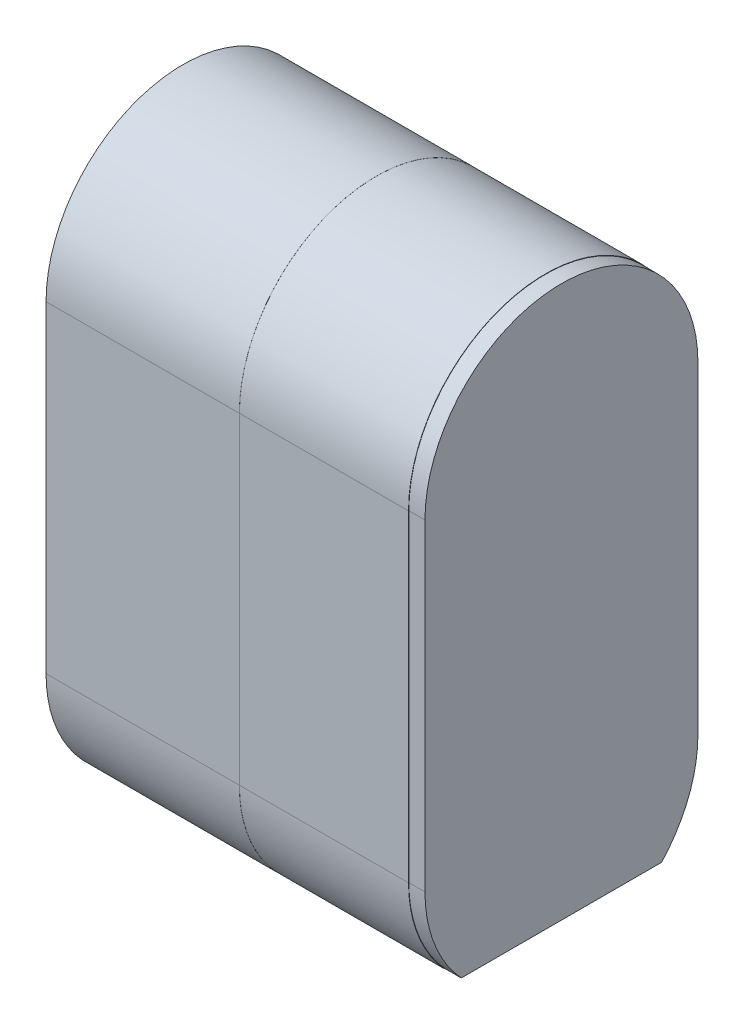
SolidWorks part; units mm, degrees
ref_plane "Front Plane" through (0, 0, 0) normal (0, 0, 1) x (1, 0, 0)
ref_plane "Top Plane" through (0, 0, 0) normal (0, 1, 0) x (1, 0, 0)
ref_plane "Right Plane" through (0, 0, 0) normal (1, 0, 0) x (0, 0, -1)
sketch "Sketch1" plane through (0, 0, 0) normal (1, 0, 0) x (0, 0, -1)
  line L0 (0, 0) -> (0, -40) construction
  line L1 (17, 0) -> (17, -40)
  line L2 (-17, 0) -> (-17, -40)
  line L3 (0, 0) -> (0, -40) construction
  line L4 (15, 0) -> (15, -40)
  line L5 (-15, 0) -> (-15, -40)
  arc A0 (17, 0) -> (-17, 0) centre (0, 0) ccw
  arc A1 (-17, -40) -> (17, -40) centre (0, -40) ccw
  arc A2 (15, 0) -> (-15, 0) centre (0, 0) ccw
  arc A3 (-15, -40) -> (15, -40) centre (0, -40) ccw
  point P3 (0, -20)
  point P8 (0, -20)
  dimension "D1" = 2
  dimension "D2" = 40
  dimension "D3" = 30
extrude "Boss-Extrude1" add sketch "Sketch1" along normal blind 20 and the other way blind 2
sketch "Sketch3" plane through (-2, 0, 0) normal (-1, 0, 0) x (0, 0, 1)
  line L0 (0, -55) -> (0, 15) construction
  line L1 (17, -20) -> (-17, -20) construction
  line L2 (17, 0) -> (17, -40) construction
  line L3 (-17, -40) -> (-17, 0) construction
  arc A0 (-15, -40) -> (15, -40) centre (0, -40) ccw construction
  arc A1 (15, 0) -> (-15, 0) centre (0, 0) ccw construction
sketch "Sketch4" plane through (20, 0, 0) normal (1, 0, 0) x (0, 0, -1)
  line L0 (-11.6154, -49.4912) -> (-12.5, -49.4912)
  line L1 (-12.5, -49.4912) -> (12.5, -49.4912) construction
  line L2 (-12.5, -49.4912) -> (-12.5, -51.4912)
  line L3 (-12.5, -49.4912) -> (-12.5, -51.4912) construction
  line L4 (-12.5, -51.4912) -> (12.5, -51.4912) construction
  line L6 (-9.6412, -51.4912) -> (-9.5741, -51.4912)
  line L7 (11.6154, -49.4912) -> (12.5, -49.4912)
  line L8 (12.5, -49.4912) -> (12.5, -51.4912) construction
  line L9 (12.5, -49.4912) -> (12.5, -51.4912)
  line L10 (-12.5, -49.4912) -> (12.5, -49.4912)
  line L11 (-12.5, -49.4912) -> (-12.5, -57.4121)
  line L12 (-12.5, -57.4121) -> (12.5, -57.4121)
  line L13 (12.5, -49.4912) -> (12.5, -57.4121)
  arc A0 (-15, -40) -> (15, -40) centre (0, -40) ccw construction
extrude "Cut-Extrude3" cut sketch "Sketch4" against normal through all
sketch "Sketch5" plane through (-2, 0, 0) normal (-1, 0, 0) x (0, 0, 1)
  line L0 (0, 0) -> (0, -40) construction
  line L1 (17, 0) -> (17, -40)
  line L2 (-17, 0) -> (-17, -40)
  line L8 (-12.5, -51.5217) -> (12.5, -51.5217)
  arc A0 (17, 0) -> (-17, 0) centre (0, 0) ccw
  arc A1 (-17, -40) -> (-12.5, -51.5217) centre (0, -40) ccw
  arc A2 (-17, -40) -> (-12.5, -51.5217) centre (0, -40) ccw construction
  arc A3 (12.5, -51.5217) -> (17, -40) centre (0, -40) ccw
  point P4 (0, -20)
extrude "Boss-Extrude2" add sketch "Sketch5" along normal blind 2
sketch "Sketch6" plane through (-4, 0, 0) normal (-1, 0, 0) x (0, 0, 1)
  circle A0 centre (-0.05, -8.0912) radius 15
extrude "Cut-Extrude4" cut sketch "Sketch6" against normal through all
sketch "Sketch7" plane through (20, 0, 0) normal (1, 0, 0) x (0, 0, -1)
  line L0 (0, 0) -> (0, -40) construction
  line L1 (-12.5, -49.4912) -> (-11.61, -49.4912)
  line L2 (-12.5, -49.4912) -> (-12.5, -51.5217)
  line L3 (-12.5, -51.5217) -> (-12.4883, -51.5217)
  line L4 (12.5, -49.4912) -> (12.5, -51.5217)
  line L5 (15.0996, 0) -> (14.9958, -40)
  line L6 (-15.0996, 0) -> (-14.9958, -40)
  line L7 (0, 0) -> (0, -40) construction
  line L8 (16.9914, 0) -> (16.9914, -40)
  line L9 (-16.9914, 0) -> (-16.9914, -40)
  line L10 (12.4883, -51.5217) -> (12.5, -51.5217)
  line L11 (11.61, -49.4912) -> (12.5, -49.4912)
  arc A0 (15.0996, 0) -> (-15.0996, 0) centre (0, 0) ccw
  arc A1 (-14.9958, -40) -> (-11.61, -49.4912) centre (0, -40) ccw
  arc A2 (16.9914, 0) -> (-16.9914, 0) centre (0, 0) ccw
  arc A3 (-16.9914, -40) -> (-12.4883, -51.5217) centre (0, -40) ccw
  arc A4 (12.4883, -51.5217) -> (16.9914, -40) centre (0, -40) ccw
  arc A5 (11.61, -49.4912) -> (14.9958, -40) centre (0, -40) ccw
  point P10 (0, -20)
  point P15 (0, -20)
  line M10 (15, -9.3149) -> (15, -40)
  arc M11 (15, -40) -> (11.6154, -49.4912) centre (0, -40) cw
  line M12 (11.6154, -49.4912) -> (12.5, -49.4912)
  line M13 (12.5, -49.4912) -> (12.5, -51.5217)
  line M20 (-12.5, -49.4912) -> (-11.6154, -49.4912)
  arc M21 (-11.6154, -49.4912) -> (-15, -40) centre (0, -40) cw
  line M22 (-15, -40) -> (-15, 0)
extrude "Boss-Extrude3" add sketch "Sketch7" along normal blind 21 separate body contours A4 L8 A2 L9 A3 L2 L6 A0 L5 M13 M20 M21 M22 M10 M11 M12
sketch "Sketch10" plane through (41, 0, 0) normal (1, 0, 0) x (0, 0, -1)
  line L0 (0, -40) -> (0, 0) construction
  line L3 (-16.948, -40) -> (-16.948, 0)
  line L8 (16.948, -40) -> (16.948, 0)
  line L9 (12.4409, -51.509) -> (12.5, -51.509)
  line L11 (-12.5, -51.4448) -> (-12.5, -51.509)
  line L12 (-12.5, -51.509) -> (-12.4409, -51.509)
  line L13 (12.5, -51.4448) -> (12.5, -51.509)
  line L14 (-12.4409, -51.509) -> (12.4409, -51.509)
  arc A2 (-16.948, -40) -> (-12.4409, -51.509) centre (0, -40) ccw
  arc A3 (16.948, 0) -> (-16.948, 0) centre (0, 0) ccw
  arc A4 (12.4409, -51.509) -> (16.948, -40) centre (0, -40) ccw
  point P4 (0, -20)
  point P5 (0, -20)
extrude "Boss-Extrude5" add sketch "Sketch10" along normal blind 2
